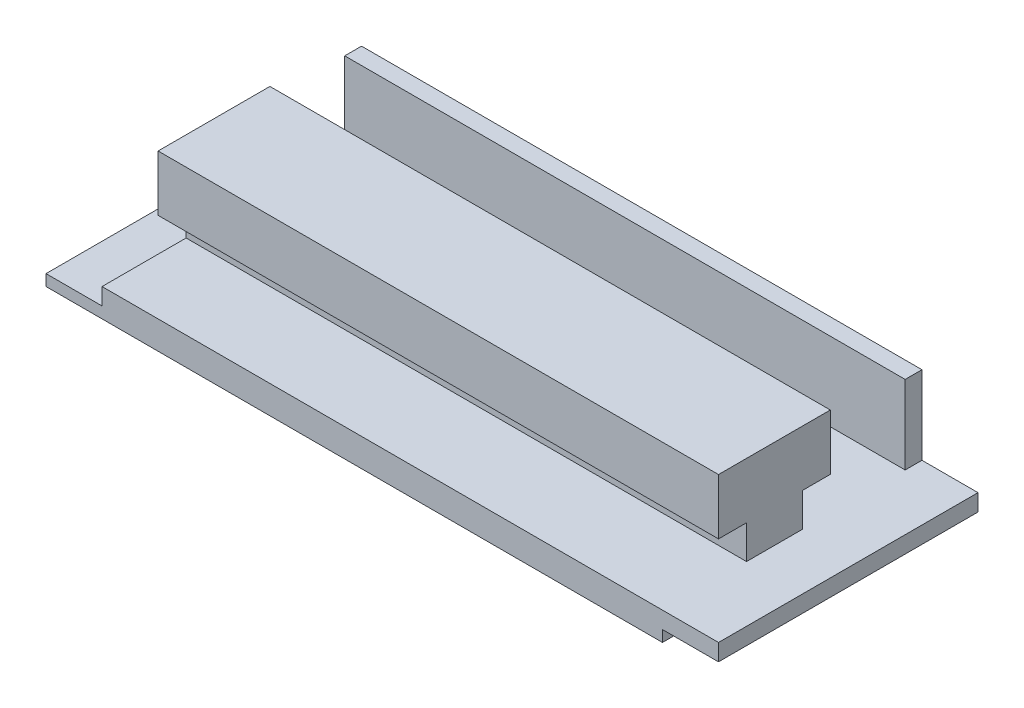
SolidWorks part; units mm, degrees
ref_plane "Front Plane" through (0, 0, 0) normal (0, 0, 1) x (1, 0, 0)
ref_plane "Top Plane" through (0, 0, 0) normal (0, 1, 0) x (1, 0, 0)
ref_plane "Right Plane" through (0, 0, 0) normal (1, 0, 0) x (0, 0, -1)
sketch "Sketch2" plane through (0, 5.9414, 0) normal (1, 0, 0) x (0, 0, -1)
  line L0 (-15.5389, 15.9499) -> (4.4111, 15.9499)
  line L1 (-15.5389, 15.9499) -> (-15.5389, 5.9999)
  line L2 (-15.5389, 5.9999) -> (-10.5389, 5.9999)
  line L3 (-10.5389, 5.9999) -> (-10.5389, 0)
  line L5 (-10.5389, 0) -> (-0.5889, 0)
  line L6 (-0.5889, 0) -> (-0.5889, 6)
  line L7 (-0.5889, 6) -> (4.4111, 6)
  line L9 (4.4111, 6) -> (4.4111, 15.9499)
  line L10 (-10.5389, 0) -> (-25.5389, 0)
  line L11 (-25.5389, 0) -> (-25.5389, -5)
  line L12 (-25.5389, -5) -> (4.7634, -5)
  line L13 (4.7634, -5) -> (4.7634, 0)
  line L14 (4.7634, 0) -> (4.7634, -5)
  line L15 (4.7634, -5) -> (17.7634, -5)
  line L16 (17.7634, -5) -> (17.7634, 0)
  line L17 (17.7634, 0) -> (4.7634, 0)
  line L18 (17.7634, -5) -> (20.7634, -5)
  line L19 (20.7634, -5) -> (20.7634, 14)
  line L20 (20.7634, 14) -> (17.7634, 14)
  line L21 (17.7634, 14) -> (17.7634, 0)
  line L22 (-0.5889, 0) -> (4.7634, 0)
  dimension "D1" = 9.95
  dimension "D2" = 5
  dimension "D3" = 5
  dimension "D4" = 9.95
  dimension "D5" = 9.9499
  dimension "D6" = 19.95
extrude "Boss-Extrude1" add sketch "Sketch2" along normal blind 100 contours L7 L9 L0 L1 L2 L3 L5 L6 | L20 L21 L16 L18 L19 | L22 L5 L10 L11 L12 L13 | L16 L17 L13 L15
sketch "Sketch4" plane through (0, 0, 0) normal (-1, 0, 0) x (0, 0, 1)
  line L0 (-20.7634, 2.9414) -> (25.5389, 2.9414)
  line L1 (-20.7634, 0.9414) -> (-20.7634, 19.9414) construction
  line L2 (25.5389, 5.9414) -> (25.5389, 0.9414) construction
  line L3 (25.5389, 2.9414) -> (25.5389, 0.9414)
  line L4 (25.5389, 0.9414) -> (-20.7634, 0.9414)
  line L5 (-20.7634, 0.9414) -> (-20.7634, 2.9414)
extrude "Boss-Extrude2" add sketch "Sketch4" along normal blind 10 contours L5 L0 L3 L4
sketch "Sketch5" plane through (100, 0, 0) normal (1, 0, 0) x (0, 0, -1)
  line L0 (-25.5389, 0.9414) -> (-25.5389, 2.9414)
  line L1 (-25.5389, 2.9414) -> (20.7634, 2.9414)
  line L2 (20.7634, 2.9414) -> (20.7634, 0.9414)
  line L3 (-25.5389, 0.9414) -> (-25.5389, 2.9414)
  line L5 (-25.5389, 2.9414) -> (-25.5389, 5.9414)
  line L6 (-25.5389, 5.9414) -> (-25.5389, 0.9414) construction
  line L7 (-25.5389, 5.9414) -> (20.7634, 5.9414)
  line L8 (20.7634, 0.9414) -> (20.7634, 19.9414) construction
  line L9 (20.7634, 5.9414) -> (20.7634, 2.9414)
  line M6 (17.7634, 5.9414) -> (-0.5889, 5.9414)
  line M14 (-10.5389, 5.9414) -> (-25.5389, 5.9414)
  line M15 (-25.5389, 5.9414) -> (-25.5389, 0.9414)
  line M17 (20.7634, 0.9414) -> (20.7634, 19.9414)
extrude "Boss-Extrude4" add sketch "Sketch5" along normal blind 10 contours L7 L1 M14 M15 M17 M6
